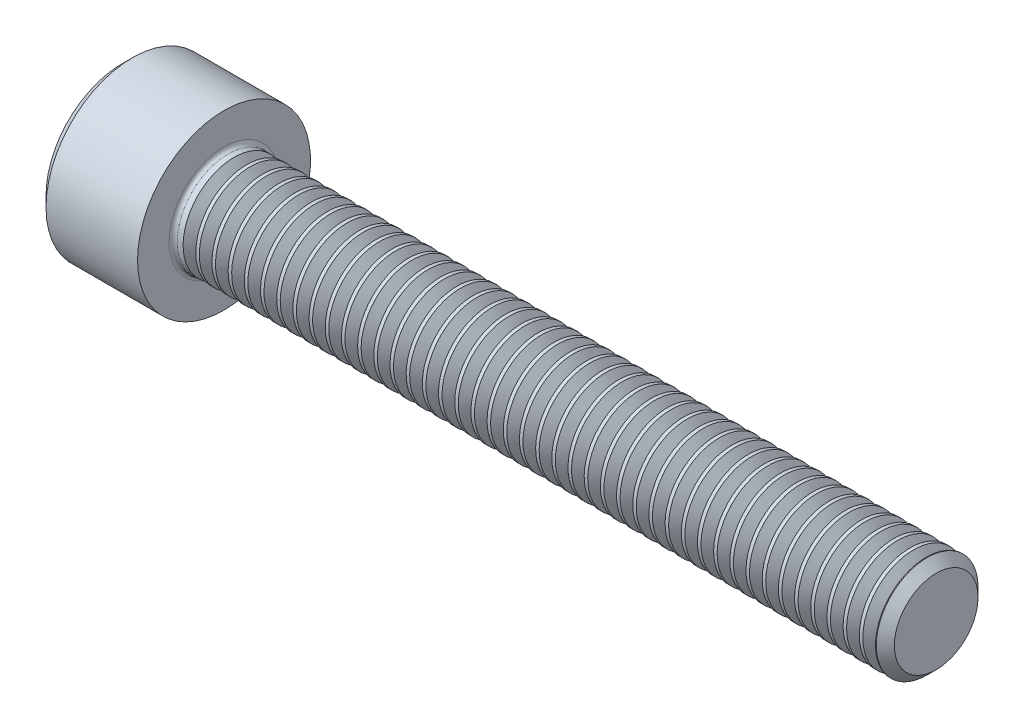
SolidWorks part; units mm, degrees
revolve "Base-Revolve" add sketch "BodySke"
sketch "BodySke" plane through (0, 0, 0) normal (0, 0, 1) x (1, 0, 0)
  line L0 (0, 0) -> (0, 3.75)
  line L1 (0.5, 4.25) -> (5, 4.25)
  line L2 (5, 4.25) -> (5, 2.5)
  line L3 (5, 2.5) -> (39.555, 2.5)
  line L4 (40, 2.055) -> (40, 0)
  line L5 (40, 0) -> (0, 0)
  line L6 (-31.75, 0) -> (127, 0) construction
  line L7 (0, 3.75) -> (0.5, 4.25)
  line L8 (40, 2.055) -> (39.555, 2.5)
  line L9 (0, -3.75) -> (0.5, -4.25) construction
  line L10 (40, -2.055) -> (39.555, -2.5) construction
  line L11 (5.8, 9.525) -> (5.8, 3.175) construction
  line L12 (5, 9.525) -> (5, 3.175) construction
  line L13 (-10, 9.525) -> (-10, 3.175) construction
  dimension "Diameter" = 5
  dimension "Head_ht" = 5
  dimension "Length" = 35
  dimension "Body_ch_ang" = 45
  dimension "Head_dia" = 8.5
  dimension "Head_ch_ang" = 45
  dimension "Minor_dia" = 4.11
  dimension "Advance" = 0.8
  dimension "Thread_nom" = 35
  dimension "Thread_length" = 50
  dimension "Head_ch_ht" = 0.5
cosmetic thread "ThreadCosmetic" [suppressed]
fillet "Fillet1" radius 0.2 1 edges at (5, 0, 2.5)
ref_plane "Plane1" through (0, 0, 0) normal (0, 0, 1) x (1, 0, 0)
ref_plane "Plane2" through (0, 0, 0) normal (0, 1, 0) x (1, 0, 0)
ref_plane "Plane3" through (0, 0, 0) normal (1, 0, 0) x (0, 0, -1)
sketch "Sketch2" plane through (0, 0, 0) normal (0, 0, 1) x (1, 0, 0)
  line L0 (0, 2.042) -> (2.5, 2.042)
  line L1 (2.5, 2.042) -> (3.6789, 0)
  line L2 (-31.75, 0) -> (127, 0) construction
  line L3 (3.6789, 0) -> (0, 0)
  line L4 (0, 0) -> (0, 2.042)
  line L5 (0, 3.75) -> (0, -3.75) construction
  line L6 (0, 0) -> (47.625, 0) construction
  line L7 (5, -4.25) -> (5, 4.25) construction
  dimension "D1" = 2.042
  dimension "D2" = 60
revolve "Hex-PreBroach" cut sketch "Sketch2" angle 360 about L6
sketch "Sketch3" plane through (0, 0, 0) normal (-1, 0, 0) x (0, 0.5, 0.866)
  line L0 (1.1789, 2.042) -> (-1.1789, 2.042)
  line L1 (-1.1789, 2.042) -> (-2.3579, 0)
  line L2 (1.1789, 2.042) -> (2.3579, 0)
  line L3 (1.1789, -2.042) -> (2.3579, 0)
  line L4 (1.1789, -2.042) -> (-1.1789, -2.042)
  line L5 (-1.1789, -2.042) -> (-2.3579, 0)
  dimension "D1" = 2.042
  dimension "D2" = 2.042
  dimension "Hex_size" = 4.084
extrude "Hex" cut sketch "Sketch3" against normal blind 2.5
sketch "Sketch4" plane through (0, 0, 0) normal (-1, 0, 0) x (0, 0, 1)
  line L0 (0, 0) -> (2.3876, 0)
  line L1 (0, 0) -> (6.1484, 3.5498) construction
  line L2 (0, 0) -> (1.1938, 2.0677)
  line L3 (1.9883, 0.576) -> (2.2704, 0.7389)
  line L4 (1.493, 1.4339) -> (1.7751, 1.5968)
  arc A0 (1.9883, 0.576) -> (1.493, 1.4339) centre (0, 0) ccw
  arc A1 (2.3876, 0) -> (2.2704, 0.7389) centre (0, 0) ccw
  arc A2 (1.1938, 2.0677) -> (1.7751, 1.5968) centre (0, 0) cw
  dimension "D1" = 30
  dimension "D2" = 60
  dimension "Spline_p_dim" = 0.9906
  dimension "D3" = 0.4953
extrude "Spline" [suppressed] cut sketch "Sketch4" against normal blind 2.5
pattern_circular "CirPattern1" [suppressed] count 6 over 360
sketch "Sketch5" plane through (0, 0, 0) normal (0, 0, 1) x (1, 0, 0)
  line L0 (-31.75, 0) -> (127, 0) construction
  line L2 (0, 3.75) -> (0, -3.75) construction
  circle A0 centre (2, 0) radius 0.675
  dimension "Drilled_hole_dia" = 1.35
  dimension "Drilled_hole_loc" = 2
extrude "Hole" [suppressed] cut sketch "Sketch5" against normal through all and the other way through all
pattern_circular "Drilled-4" [suppressed] count 2 every 60
pattern_circular "Drilled-6" [suppressed] count 3 every 60
sketch "ThdSchSke" plane through (0, 0, 0) normal (0, 0, 1) x (1, 0, 0)
  line L0 (5.8, -2.055) -> (5.4884, -2.5)
  line L1 (5.8, -2.055) -> (6.1116, -2.5)
  line L2 (6.1116, -2.5) -> (6.1116, -3.125)
  line L3 (-3.175, 0) -> (5.1513, 0) construction
  line L5 (6.1116, -3.125) -> (5.4884, -3.125)
  line L6 (5.4884, -3.125) -> (5.4884, -2.5)
  line L7 (0, 3.75) -> (0, -3.75) construction
  dimension "Thread_minor" = 4.11
  dimension "Diameter" = 5
  dimension "Start" = 5.8
revolve "ThreadSchematic" cut sketch "ThdSchSke" angle 360 about L3
pattern_linear "ThdSchPat" count 43 spacing 0.7953 along (1, 0, 0) of "ThreadSchematic"
equation "\"D2@Sketch3\" = \"Hex_size@Sketch3\" / 2"
equation "\"D1@Sketch3\" = \"Hex_size@Sketch3\" / 2"
equation "\"D1@Sketch2\" = \"Hex_size@Sketch3\" / 2"
equation "\"D3@Sketch4\" = \"Spline_p_dim@Sketch4\" / 2"
equation "\"Thread_minor@ThreadCosmetic\"  =  \"Minor_dia@BodySke\""
equation "\"D2@CirPattern1\" = 360 / \"Num_teeth@CirPattern1\""
equation "\"Wall_thickness@Sketch2\" = \"Head_ht@BodySke\" - \"Key_eng@Hex\""
equation "\"Thread_length@ThreadCosmetic\" = ((sgn( (\"Length@BodySke\" - \"Advance@BodySke\" ) - \"Thread_nom@BodySke\" )-1)*( (\"Length@BodySke\" - \"Advance@BodySke\" ) - \"Thread_nom@BodySke\" ))/-2+ \"Thread_nom@BodySke\""
equation "\"Thread_minor@ThdSchSke\" = \"Minor_dia@BodySke\""
equation "\"Diameter@ThdSchSke\" = \"Diameter@BodySke\""
equation "\"Overcut@ThdSchSke\" = \"Diameter@BodySke\" * 1.25"
equation "\"Start@ThdSchSke\" = \"Head_ht@BodySke\" + \"Length@BodySke\" - \"Thread_length@ThreadCosmetic\"  '---Non-countersunk---"
equation "\"Num_threads@ThdSchPat\" = int( \"Thread_length@ThreadCosmetic\" / \"Advance@BodySke\" + 0.999 )  + 1"
equation "\"Advance@ThdSchPat\" = \"Thread_length@ThreadCosmetic\" /  (\"Num_threads@ThdSchPat\" - 1) 'relax it"
equation "\"Num_threads@ThdSchPat\" = \"Num_threads@ThdSchPat\" - sgn( \"Num_threads@ThdSchPat\" - 1) '---chamfered tips only---"
